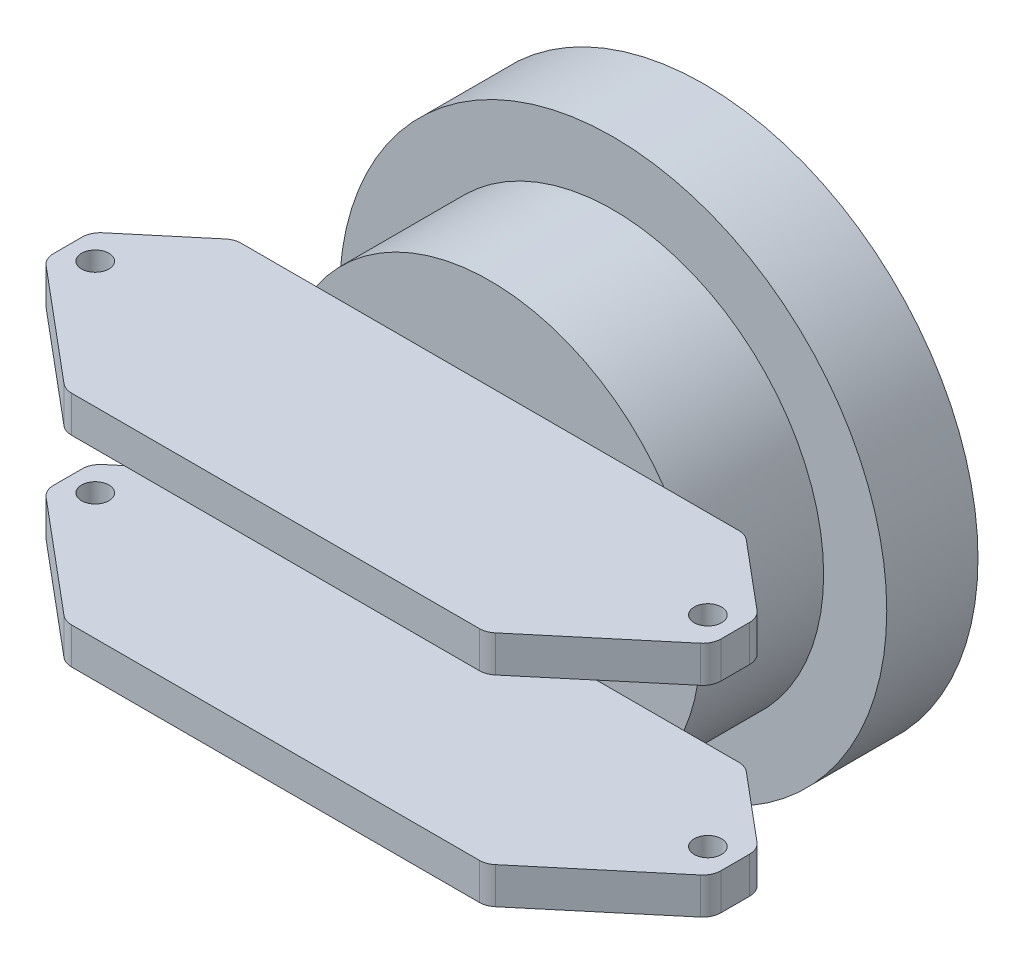
SolidWorks part; units mm, degrees
ref_plane "Front" through (0, 0, 0) normal (0, 0, 1) x (1, 0, 0)
ref_plane "Top" through (0, 0, 0) normal (0, 1, 0) x (1, 0, 0)
ref_plane "Right" through (0, 0, 0) normal (1, 0, 0) x (0, 0, -1)
sketch "Sketch1" plane through (0, 0, 0) normal (0, 0, 1) x (1, 0, 0)
  circle A0 centre (0, 0) radius 30
  dimension "D1" = 60
extrude "Boss-Extrude1" add sketch "Sketch1" along normal blind 10
sketch "Sketch2" plane through (0, 0, 10) normal (0, 0, 1) x (1, 0, 0)
  circle A0 centre (0, 0) radius 23.08
extrude "Boss-Extrude2" add sketch "Sketch2" along normal blind 13.4862 contours A0
ref_plane "Plane1" through (0, 13, 0) normal (0, 1, 0) x (1, 0, 0)
sketch "Sketch4" plane through (0, 13, 0) normal (0, 1, 0) x (1, 0, 0)
  line L0 (0, -23.4862) -> (-48.9101, -23.4862) construction
  line L1 (-23.08, -23.4862) -> (23.08, -23.4862) construction
  line L2 (28, -23.4862) -> (-28, -23.4862)
  line L3 (-28, -23.4862) -> (-36.5797, -30.6854)
  line L4 (-36.5797, -30.6854) -> (-36.5797, -35.6854)
  line L5 (-23.08, -23.4862) -> (-23.08, -83.02) construction
  line L6 (-23.08, -10) -> (-23.08, -23.4862) construction
  line L7 (-36.5797, -35.6854) -> (-23.08, -47.013)
  line L8 (-36.5797, -35.6854) -> (-36.5797, -54.4246) construction
  line L9 (-23.08, -47.013) -> (23.08, -47.013)
  line L10 (0, -23.4862) -> (0, -50.8219) construction
  line L11 (36.5797, -35.6854) -> (23.08, -47.013)
  line L12 (36.5797, -30.6854) -> (36.5797, -35.6854)
  line L13 (28, -23.4862) -> (36.5797, -30.6854)
  point P17 (0, -47.013)
  dimension "D1" = 28
  dimension "D2" = 40
  dimension "D3" = 5
  dimension "D4" = 11.2
  dimension "D5" = 50
extrude "Boss-Extrude3" add sketch "Sketch4" against normal blind 4
fillet "Fillet1" radius 2 8 edges at (-28, 11, 23.4862) (28, 11, 23.4862) (36.5797, 11, 30.6854) (36.5797, 11, 35.6854) (23.08, 11, 47.013) (-23.08, 11, 47.013) (-36.5797, 11, 35.6854) (-36.5797, 11, 30.6854)
sketch "Sketch5" plane through (0, 13, 0) normal (0, 1, 0) x (1, 0, 0)
  line L0 (-36.5797, -33.1854) -> (-33.5797, -33.1854) construction
  line L1 (-36.5797, -31.618) -> (-36.5797, -34.7528) construction
  circle A0 centre (-33.5797, -33.1854) radius 1.5
  dimension "D2" = 3
  dimension "D1" = 3
extrude "Cut-Extrude1" cut sketch "Sketch5" against normal blind 4
mirror "Mirror1" about plane through (0, 0, 0) normal (1, 0, 0) of "Cut-Extrude1"
mirror "Mirror2" about plane through (0, 0, 0) normal (0, 1, 0) of "Mirror1", "Cut-Extrude1", "Fillet1", "Boss-Extrude3"
sketch "Sketch8" plane through (0, 0, 0) normal (0, 0, -1) x (-1, 0, 0)
  circle A0 centre (0, 0) radius 7.5
  dimension "D1" = 15
extrude "Cut-Extrude2" cut sketch "Sketch8" against normal blind 10
ref_plane "Plane2" through (0, 0, 0) normal (0, 0, -1) x (-1, 0, 0)
sketch "Sketch9" plane through (0, 0, 0) normal (0, 0, -1) x (-1, 0, 0)
  line L0 (-70, 0) -> (0, 0) construction
  line L1 (0, 0) -> (0, 70) construction
  text T0 "X3\r\n\r\n" font "Century Gothic" height 20
  text T1 "Y3\r\n\r\n\r\n" font "Century Gothic" height 20
  dimension "D1" = 70
sketch "Sketch10" plane through (0, 0, 0) normal (0, 1, 0) x (1, 0, 0)
  line L0 (0, 0) -> (0, -70) construction
  line L1 (70, 0) -> (0, 0) construction
  text T0 "Z3\r\n" font "Century Gothic" height 20
ref_plane "Plane3" through (0, 0, 77) normal (0, 0, -1) x (-1, 0, 0)
sketch "Sketch11" plane through (0, 0, 77) normal (0, 0, -1) x (-1, 0, 0)
  line L0 (0, 70) -> (0, 0) construction
  line L1 (0, 0) -> (-70, 0) construction
  line L2 (0, 0) -> (0, 70) construction
  line L3 (-70, 0) -> (0, 0) construction
  text T0 "X4\r\n" font "Century Gothic" height 20
  text T1 "Y4\r\n" font "Century Gothic" height 20
  point P2 (0, 0)
  point P4 (0, 0)
  point P5 (0, 0)
  point P7 (70, 0)
  point P10 (69.7892, -5.4288)
  point P14 (0, 0)
sketch "Sketch12" plane through (0, 0, 0) normal (1, 0, 0) x (0, 0, -1)
  line L0 (-77, 0) -> (-147, 0) construction
  line L1 (-77, 70) -> (-77, 0) construction
  text T0 "Z4\r\n" font "Century Gothic" height 20
  point P6 (0, 0)
  point P7 (-78.1874, 0)
  point P8 (0, 0)
  point P9 (0, 0)
